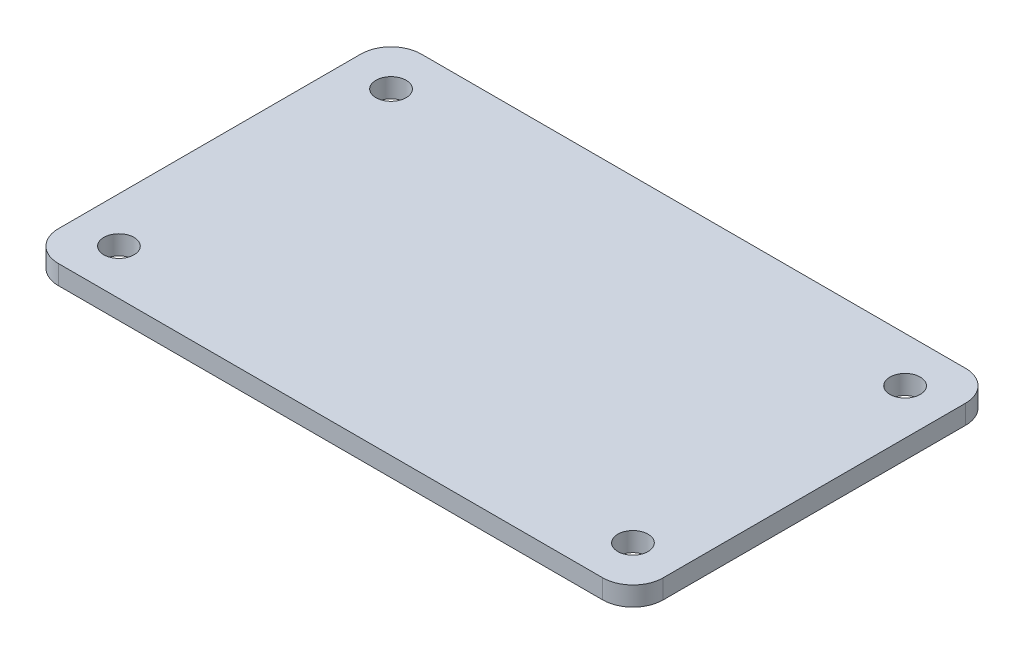
SolidWorks part; units mm, degrees
ref_plane "Plan de face" through (0, 0, 0) normal (0, 0, 1) x (1, 0, 0)
ref_plane "Plan de dessus" through (0, 0, 0) normal (0, 1, 0) x (1, 0, 0)
ref_plane "Plan de droite" through (0, 0, 0) normal (1, 0, 0) x (0, 0, -1)
sketch "Esquisse1" plane through (0, 0, 0) normal (0, 1, 0) x (1, 0, 0)
  line L1 (-100, -60) -> (100, -60)
  line L2 (-100, -60) -> (-100, 60)
  line L3 (-100, 60) -> (100, 60)
  line L4 (100, -60) -> (100, 60)
  line L5 (-100, -60) -> (100, 60) construction
  line L6 (-100, 60) -> (100, -60) construction
  point P0 (0, 0)
  dimension "D1" = 200
  dimension "D2" = 120
extrude "Boss.-Extru.1" add sketch "Esquisse1" along normal blind 6.35
sketch "Esquisse2" plane through (0, 6.35, 0) normal (0, 1, 0) x (1, 0, 0)
  line L0 (100, -60) -> (100, 60) construction
  line L1 (-85, 45) -> (85, 45) construction
  line L2 (-85, 45) -> (-85, -45) construction
  line L3 (-85, -45) -> (85, -45) construction
  line L4 (85, 45) -> (85, -45) construction
  line L5 (-100, -60) -> (100, -60) construction
  line L6 (0, -3.4925) -> (0, 3.4925) construction
  line L7 (-3.4925, 0) -> (3.4925, 0) construction
  point P8 (0, -45)
  point P11 (85, 0)
  dimension "D1" = 15
  dimension "D2" = 15
hole_wizard "Diamètre du perçage Ø10.0 (10)1" positions "Esquisse3" profile "Esquisse4" hole size "Ø10.0" standard "Ansi Metric" end condition through all
sketch "Esquisse3" plane through (0, 6.35, 0) normal (0, 1, 0) x (1, 0, 0)
  point P0 (-85, 45)
  point P3 (-85, -45)
  point P6 (85, -45)
  point P9 (85, 45)
sketch "Esquisse4" plane through (-85, 6.35, -45) normal (1, 0, 0) x (0, 0, 1)
  line L0 (0, 0) -> (0, 6.35)
  line L1 (0, 6.35) -> (5, 6.35)
  line L2 (5, 6.35) -> (5, 0)
  line L5 (5, 0) -> (0, 0)
  line L11 (0, -6.35) -> (0, 107.95) construction
  dimension "Diamètre du perçage jusqu'au prochain" = 10
  dimension "Profondeur du perçage jusqu'au prochain" = 6.35
fillet "Congé1" radius 10 4 edges at (-100, 3.175, -60) (-100, 3.175, 60) (100, 3.175, 60) (100, 3.175, -60)
